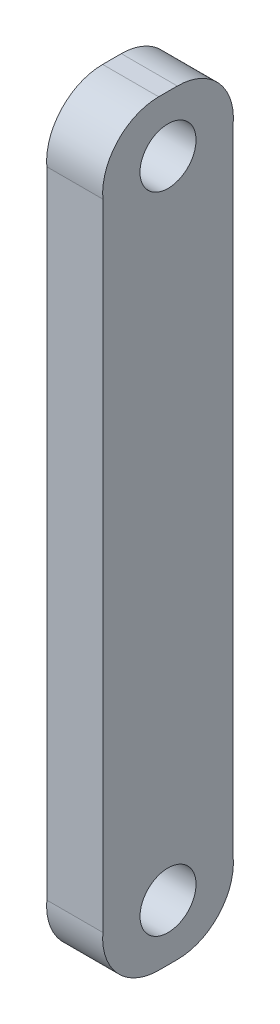
SolidWorks part; units mm, degrees
material "Plain Carbon Steel"
ref_plane "Front Plane" through (0, 0, 0) normal (0, 0, 1) x (1, 0, 0)
ref_plane "Top Plane" through (0, 0, 0) normal (0, 1, 0) x (1, 0, 0)
ref_plane "Right Plane" through (0, 0, 0) normal (1, 0, 0) x (0, 0, -1)
sketch "Sketch1" plane through (0, 0, 0) normal (1, 0, 0) x (0, 0, -1)
  line L0 (0, 0) -> (0.5, 0) construction
  line L1 (0, 0) -> (-0.5, 0) construction
  line L2 (-0.5, -3) -> (0.5, -3)
  line L3 (3.4895, 0.2509) -> (3.4895, 34.2509)
  line L4 (-3.4895, 0.2509) -> (-3.4895, 34.2509)
  line L5 (-3.4895, 17.2509) -> (3.4895, 17.2509) construction
  line L6 (-0.5, 37.5018) -> (0.5, 37.5018)
  circle A0 centre (0, 0) radius 1.5
  arc A1 (0.5, -3) -> (3.4895, 0.2509) centre (0.5, 0) ccw
  arc A2 (-3.4895, 0.2509) -> (-0.5, -3) centre (-0.5, 0) ccw
  circle A3 centre (0, 34.5018) radius 1.5
  arc A4 (0.5, 37.5018) -> (3.4895, 34.2509) centre (0.5, 34.5018) cw
  arc A5 (-3.4895, 34.2509) -> (-0.5, 37.5018) centre (-0.5, 34.5018) cw
  dimension "D1" = 3
  dimension "D3" = 6
  dimension "D5" = 6
  dimension "D2" = 0.5
  dimension "D4" = 0.5
  dimension "D6" = 34
  dimension "D7" = 34
extrude "Boss-Extrude1" add sketch "Sketch1" along normal blind 3
